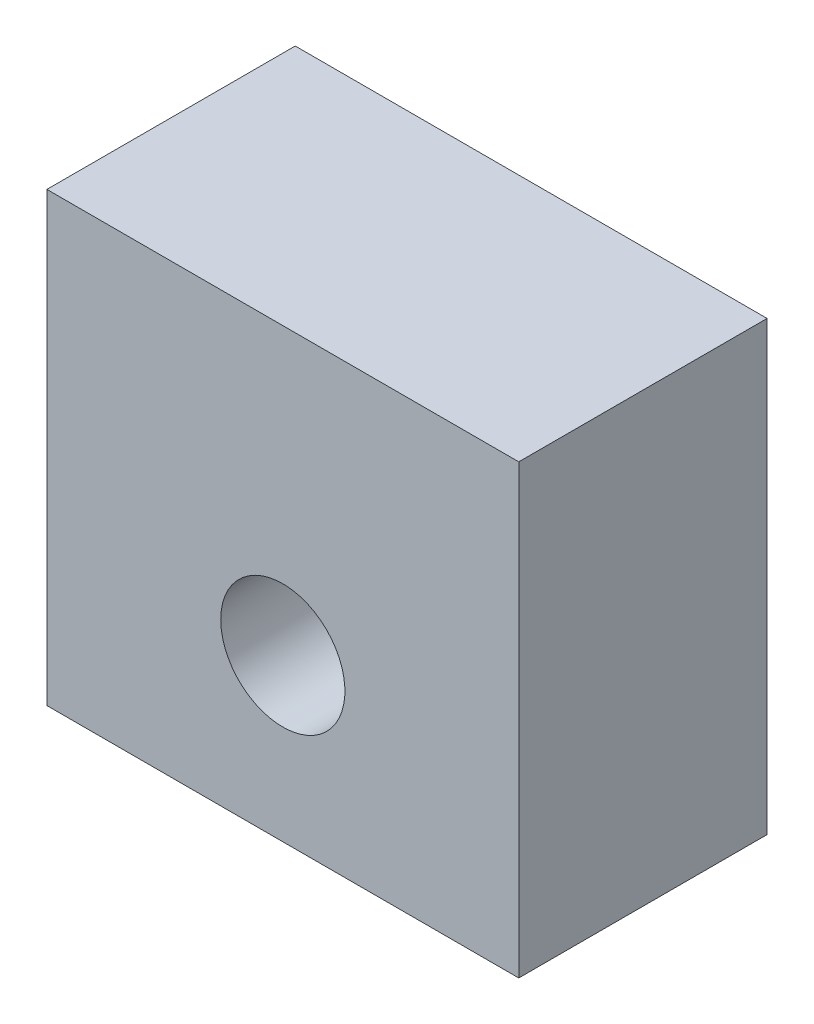
SolidWorks part; units mm, degrees
material "1060-H16"
ref_plane "Спереди" through (0, 0, 0) normal (0, 0, 1) x (1, 0, 0)
ref_plane "Сверху" through (0, 0, 0) normal (0, 1, 0) x (1, 0, 0)
ref_plane "Справа" through (0, 0, 0) normal (1, 0, 0) x (0, 0, -1)
sketch "Эскиз1" plane through (0, 0, 0) normal (0, 0, 1) x (1, 0, 0)
  line L1 (0, 0) -> (19, 0)
  line L2 (0, 0) -> (0, 18)
  line L3 (0, 18) -> (19, 18)
  line L4 (19, 0) -> (19, 18)
  dimension "D1" = 19
  dimension "D2" = 18
extrude "Бобышка-Вытянуть1" add sketch "Эскиз1" along normal blind 10
sketch "Эскиз2" plane through (0, 0, 0) normal (0, 0, -1) x (-1, 0, 0)
  line L2 (-9.5, 18) -> (-9.5, 0) construction
  line L3 (-19, 18) -> (0, 18) construction
  line L4 (0, 0) -> (-19, 0) construction
  circle A0 centre (-9.5, 6.5) radius 2.5
  dimension "D1" = 6.5
  dimension "D2" = 5
extrude "Вырез-Вытянуть1" cut sketch "Эскиз2" against normal through all
